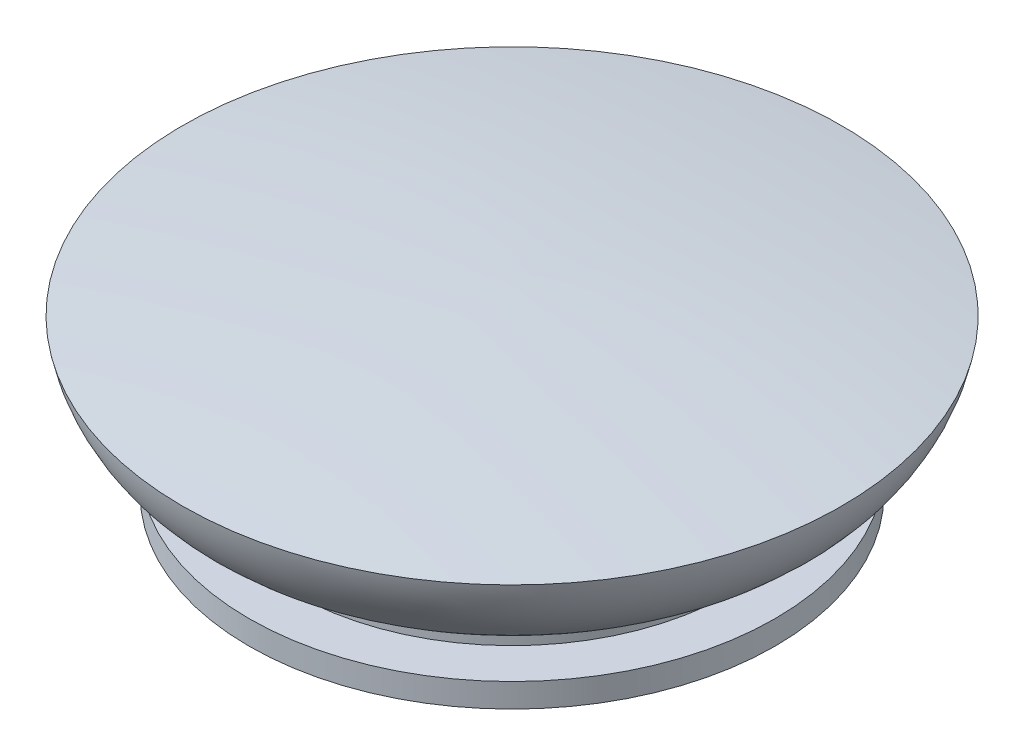
SolidWorks part; units mm, degrees
ref_plane "Front Plane" through (0, 0, 0) normal (0, 0, 1) x (1, 0, 0)
ref_plane "Top Plane" through (0, 0, 0) normal (0, 1, 0) x (1, 0, 0)
ref_plane "Right Plane" through (0, 0, 0) normal (1, 0, 0) x (0, 0, -1)
sketch "Sketch1" plane through (0, 0, 0) normal (0, 0, 1) x (1, 0, 0)
  line L0 (0, 0) -> (-47.875, 0)
  line L1 (-47.875, 0) -> (-47.875, 4.35)
  line L2 (-47.875, 4.35) -> (-39.875, 4.35)
  line L3 (-39.875, 4.35) -> (-39.875, 9.35)
  line L7 (0, 28.1523) -> (0, 0)
  line L8 (0, 28.1523) -> (0, 33)
  arc A0 (-60, 28.1523) -> (0, 33) centre (8.1487, -441.5908) cw
  arc A1 (-60, 28.1523) -> (-39.875, 9.35) centre (-37.0906, 32.5018) ccw
  dimension "D1" = 4.35
  dimension "D2" = 47.875
  dimension "D3" = 60
  dimension "D4" = 5
  dimension "D5" = 33
  dimension "D6" = 8
revolve "Revolve1" add sketch "Sketch1" angle 360 about L7
